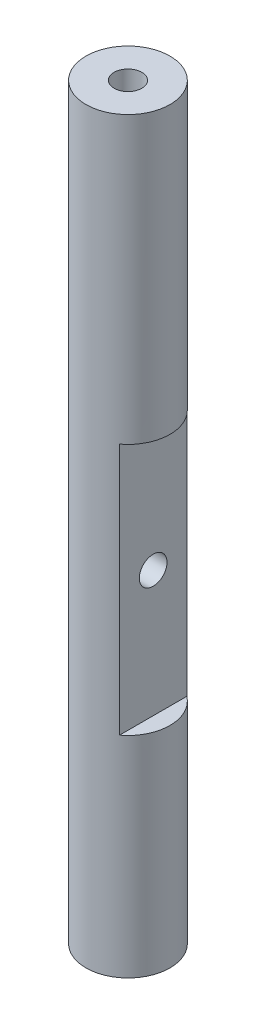
SolidWorks part; units mm, degrees
material "6061 合金"
ref_plane "前视基准面" through (0, 0, 0) normal (0, 0, 1) x (1, 0, 0)
ref_plane "上视基准面" through (0, 0, 0) normal (0, 1, 0) x (1, 0, 0)
ref_plane "右视基准面" through (0, 0, 0) normal (1, 0, 0) x (0, 0, -1)
sketch "草图1" plane through (0, 0, 0) normal (0, 1, 0) x (1, 0, 0)
  circle A0 centre (0, 0) radius 5
  dimension "D1" = 10
extrude "凸台-拉伸1" add sketch "草图1" along normal blind 89
hole_wizard "M4 螺纹孔2" positions "草图3" profile "草图2" tap size "M4" standard "GB"
sketch "草图3" plane through (0, 89, 0) normal (0, 1, 0) x (1, 0, 0)
  point P0 (0, 0)
sketch "草图2" plane through (0, 89, 0) normal (1, 0, 0) x (0, 0, 1)
  line L0 (0, 0) -> (0, 12.4914)
  line L1 (0, 12.4914) -> (1.65, 11.5)
  line L2 (1.65, 11.5) -> (1.65, 0)
  line L5 (1.65, 0) -> (0, 0)
  line L10 (0, 12.4914) -> (-1.65, 11.5) construction
  line L11 (0, -6.35) -> (0, 107.95) construction
  dimension "螺纹孔钻头直径" = 3.3
  dimension "螺纹孔钻头深度" = 11.5
  dimension "导头角度" = 118
hole_wizard "M4 螺纹孔1" positions "草图5" profile "草图6" tap size "M4" standard "GB"
sketch "草图5" plane through (0, 0, 0) normal (0, -1, 0) x (-1, 0, 0)
  point P0 (0, 0)
sketch "草图6" plane through (0, 0, 0) normal (1, 0, 0) x (0, 0, -1)
  line L0 (0, 0) -> (0, 12.4914)
  line L1 (0, 12.4914) -> (1.65, 11.5)
  line L2 (1.65, 11.5) -> (1.65, 0)
  line L5 (1.65, 0) -> (0, 0)
  line L10 (0, 12.4914) -> (-1.65, 11.5) construction
  line L11 (0, -6.35) -> (0, 107.95) construction
  dimension "螺纹孔钻头直径" = 3.3
  dimension "螺纹孔钻头深度" = 11.5
  dimension "导头角度" = 118
cosmetic thread "孔螺蚊线1" parameters "D1"=8, "D2"=4
sketch "草图7" plane through (0, 0, 0) normal (1, 0, 0) x (0, 0, -1)
  line L0 (-5, 0) -> (5, 0) construction
  line L1 (-13.3045, 25) -> (13.3045, 25)
  line L2 (-13.3045, 25) -> (-13.3045, 55)
  line L3 (-13.3045, 55) -> (13.3045, 55)
  line L4 (13.3045, 25) -> (13.3045, 55)
  line L5 (-13.3045, 25) -> (13.3045, 55) construction
  line L6 (-13.3045, 55) -> (13.3045, 25) construction
  point P0 (0, 40)
  dimension "D1" = 30
  dimension "D2" = 40
extrude "切除-拉伸1" cut sketch "草图7" against normal blind 2 from offset 5
hole_wizard "M4 螺纹孔3" positions "草图9" profile "草图8" tap size "M4" standard "GB"
sketch "草图9" plane through (3, 0, 0) normal (1, 0, 0) x (0, 0, -1)
  line L0 (-4, 25) -> (4, 25) construction
  point P0 (0, 40)
  dimension "D1" = 15
sketch "草图8" plane through (3, 40, 0) normal (0, 1, 0) x (0, 0, -1)
  line L0 (0, 0) -> (0, 12.4914)
  line L1 (0, 12.4914) -> (1.65, 11.5)
  line L2 (1.65, 11.5) -> (1.65, 0)
  line L5 (1.65, 0) -> (0, 0)
  line L10 (0, 12.4914) -> (-1.65, 11.5) construction
  line L11 (0, -6.35) -> (0, 107.95) construction
  dimension "螺纹孔钻头直径" = 3.3
  dimension "螺纹孔钻头深度" = 11.5
  dimension "导头角度" = 118
